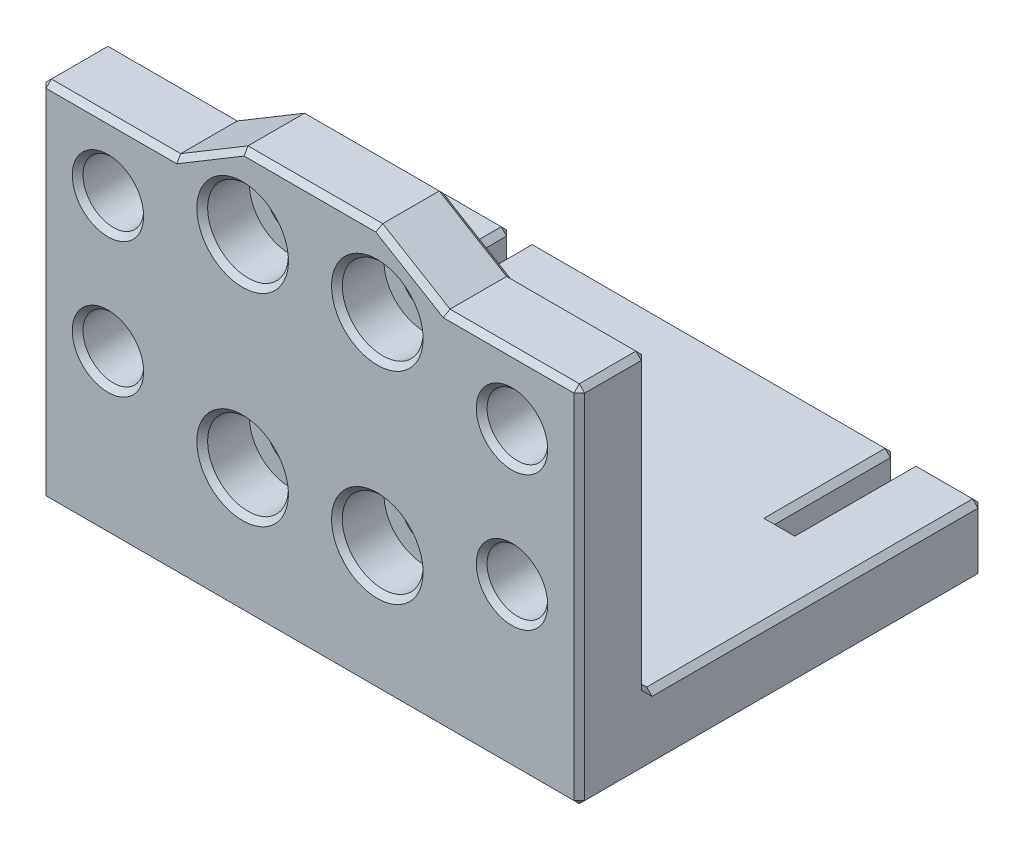
SolidWorks part; units mm, degrees
ref_plane "前视基准面" through (0, 0, 0) normal (0, 0, 1) x (1, 0, 0)
ref_plane "上视基准面" through (0, 0, 0) normal (0, 1, 0) x (1, 0, 0)
ref_plane "右视基准面" through (0, 0, 0) normal (1, 0, 0) x (0, 0, -1)
other "Configuration Table"
sketch "Sketch1" plane through (0, 0, 0) normal (0, 0, 1) x (1, 0, 0)
  line L1 (-20, -13.5) -> (20, -13.5)
  line L2 (-20, -13.5) -> (-20, 13.5)
  line L3 (-20, 13.5) -> (20, 13.5)
  line L4 (20, -13.5) -> (20, 13.5)
  line L5 (-20, -13.5) -> (20, 13.5) construction
  line L6 (-20, 13.5) -> (20, -13.5) construction
  point P0 (0, 0)
  dimension "D1" = 40
  dimension "D2" = 27
extrude "Boss-Extrude1" add sketch "Sketch1" along normal blind 5
sketch "Sketch2" plane through (0, 0, 0) normal (0, 0, -1) x (-1, 0, 0)
  line L0 (-20, -13.5) -> (-20, 13.5) construction
  line L1 (-20, -8.5) -> (20, -8.5)
  line L2 (-20, -8.5) -> (-20, -13.5)
  line L3 (-20, -13.5) -> (20, -13.5)
  line L4 (20, -8.5) -> (20, -13.5)
  line L5 (-20, 13.5) -> (20, 13.5) construction
  dimension "D1" = 22
extrude "Boss-Extrude2" add sketch "Sketch2" along normal blind 25
sketch "Sketch3" plane through (0, 0, 5) normal (0, 0, 1) x (1, 0, 0)
  line L0 (20, 13.5) -> (-20, 13.5) construction
  circle A0 centre (-5, 11) radius 1.65
  circle A1 centre (5, 11) radius 1.65
  circle A2 centre (5, -4) radius 1.65
  circle A3 centre (-5, -4) radius 1.65
  dimension "D1" = 3.3
  dimension "D2" = 2.5
  dimension "D3" = 5
  dimension "D4" = 2
  dimension "D5" = 2
extrude "Cut-Extrude1" cut sketch "Sketch3" against normal blind 15
sketch "Sketch4" plane through (0, 0, 5) normal (0, 0, 1) x (1, 0, 0)
  line L0 (-10, 13.5) -> (-5, 16.5)
  line L1 (20, 13.5) -> (-20, 13.5) construction
  line L2 (-5, 16.5) -> (5, 16.5)
  line L3 (5, 16.5) -> (10, 13.5)
  line L4 (10, 13.5) -> (-10, 13.5)
  circle A0 centre (-5, 11) radius 1.65 construction
  circle A1 centre (5, 11) radius 1.65 construction
  dimension "D1" = 5
  dimension "D2" = 5
  dimension "D3" = 5
  dimension "D4" = 5
  dimension "D5" = 3
extrude "Boss-Extrude3" add sketch "Sketch4" against normal blind 5
sketch "Sketch5" plane through (0, 0, 5) normal (0, 0, 1) x (1, 0, 0)
  circle A0 centre (-5, 11) radius 3
  circle A1 centre (5, 11) radius 3
  circle A2 centre (5, -4) radius 3
  circle A3 centre (-5, -4) radius 3
  dimension "D1" = 6
  dimension "D2" = 2
  dimension "D3" = 2
extrude "Cut-Extrude2" cut sketch "Sketch5" against normal blind 3.5
sketch "Sketch6" plane through (0, -8.5, 0) normal (0, 1, 0) x (1, 0, 0)
  line L0 (-20, 25) -> (20, 25) construction
  line L1 (-15, 25) -> (-13.5, 25)
  line L2 (-15, 25) -> (-15, 16)
  line L3 (-15, 16) -> (-13.5, 16)
  line L4 (-13.5, 25) -> (-13.5, 16)
  line L5 (-10, 0) -> (-20, 0) construction
  line L6 (13.5, 25) -> (15, 25)
  line L7 (13.5, 25) -> (13.5, 16)
  line L8 (13.5, 16) -> (15, 16)
  line L9 (15, 25) -> (15, 16)
  line L10 (-20, 25) -> (-20, 0) construction
  line L11 (20, 25) -> (20, 0) construction
  dimension "D1" = 16
  dimension "D2" = 1.5
  dimension "D3" = 1.5
  dimension "D4" = 5
  dimension "D5" = 5
extrude "Cut-Extrude3" cut sketch "Sketch6" against normal blind 5
sketch "Sketch7" plane through (0, 0, 5) normal (0, 0, 1) x (1, 0, 0)
  line L0 (-20, 13.5) -> (-20, -13.5) construction
  line L1 (-10, 13.5) -> (-20, 13.5) construction
  circle A0 centre (-15, 8.5) radius 2.25
  circle A1 centre (15, 8.5) radius 2.25
  circle A2 centre (15, -1.5) radius 2.25
  circle A3 centre (-15, -1.5) radius 2.25
  dimension "D1" = 4.5
  dimension "D2" = 5
  dimension "D3" = 5
  dimension "D4" = 2
  dimension "D5" = 2
extrude "Cut-Extrude4" cut sketch "Sketch7" against normal blind 5
chamfer "Chamfer1" distance 0.4 angle 45 62 edges at (-2, 11, 5) (8, 11, 5) (8, -4, 5) (-2, -4, 5) (-12.75, 8.5, 5) (17.25, 8.5, 5) (17.25, -1.5, 5) (-12.75, -1.5, 5) (20, 13.5, 2.5) (-15, 13.5, 5) (-7.5, 15, 5) (-7.5, 15, 0) (0, 16.5, 5) (0, 16.5, 0) (7.5, 15, 5) (7.5, 15, 0) (15, 13.5, 5) (20, 0, 5) (-20, 13.5, 2.5) (-20, 0, 5) (-20, -11, -25) (-15, -11, -25) (20, -11, -25) (15, -11, -25) (13.5, -11, -25) (-20, -13.5, -10) (0, -13.5, 5) (20, -13.5, -10) (17.5, -13.5, -25) (15, -13.5, -20.5) (14.25, -13.5, -16) (13.5, -13.5, -20.5) (0, -13.5, -25) (-17.5, -13.5, -25) (-15, -13.5, -20.5) (-14.25, -13.5, -16) (-13.5, -13.5, -20.5) (-13.5, -11, -25) (-13.5, -8.5, -20.5) (0, -8.5, -25) (13.5, -8.5, -20.5) (14.25, -8.5, -16) (15, -8.5, -20.5) (17.5, -8.5, -25) (20, -8.5, -12.5) (-14.25, -8.5, -16) (-15, -8.5, -20.5) (-17.5, -8.5, -25) (-20, -8.5, -12.5) (20, 2.5, 0) (15, 13.5, 0) (-15, 13.5, 0) (-20, 2.5, 0) (0, -8.5, 0) (-6.65, 11, 0) (3.35, 11, 0) (3.35, -4, 0) (-6.65, -4, 0) (-12.75, 8.5, 0) (17.25, 8.5, 0) (17.25, -1.5, 0) (-12.75, -1.5, 0)
